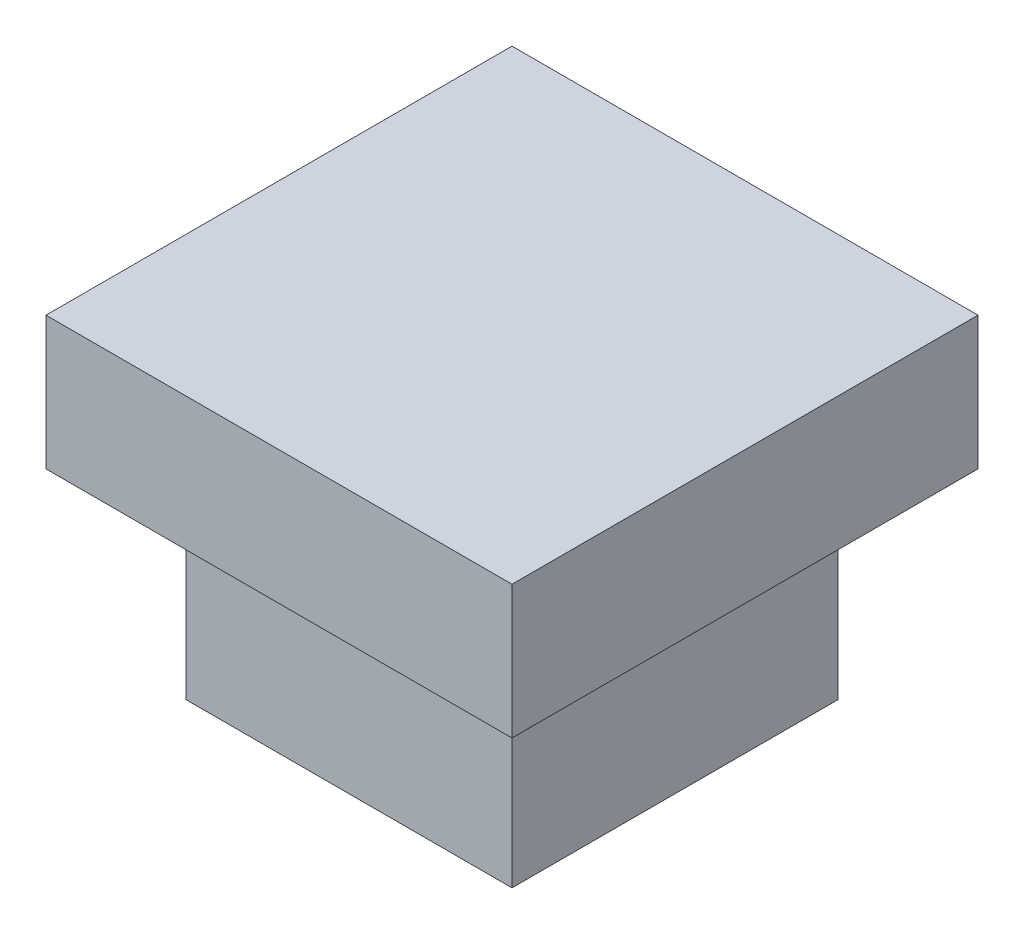
SolidWorks part; units mm, degrees
ref_plane "Alzado" through (0, 0, 0) normal (0, 0, 1) x (1, 0, 0)
ref_plane "Planta" through (0, 0, 0) normal (0, 1, 0) x (1, 0, 0)
ref_plane "Vista lateral" through (0, 0, 0) normal (1, 0, 0) x (0, 0, -1)
sketch "Croquis1" plane through (0, 0, 0) normal (0, 1, 0) x (1, 0, 0)
  line L1 (-2.45, -2.45) -> (2.45, -2.45)
  line L2 (-2.45, -2.45) -> (-2.45, 2.45)
  line L3 (-2.45, 2.45) -> (2.45, 2.45)
  line L4 (2.45, -2.45) -> (2.45, 2.45)
  line L5 (-2.45, -2.45) -> (2.45, 2.45) construction
  line L6 (-2.45, 2.45) -> (2.45, -2.45) construction
  point P0 (0, 0)
  dimension "D1" = 4.9
  dimension "D2" = 4.9
extrude "Saliente-Extruir1" add sketch "Croquis1" along normal blind 3
sketch "Croquis2" plane through (0, 3, 0) normal (0, 1, 0) x (1, 0, 0)
  line L1 (3.5, -3.5) -> (-3.5, -3.5)
  line L2 (3.5, -3.5) -> (3.5, 3.5)
  line L3 (3.5, 3.5) -> (-3.5, 3.5)
  line L4 (-3.5, -3.5) -> (-3.5, 3.5)
  line L5 (3.5, -3.5) -> (-3.5, 3.5) construction
  line L6 (3.5, 3.5) -> (-3.5, -3.5) construction
  point P0 (0, 0)
  dimension "D1" = 7
  dimension "D2" = 7
extrude "Saliente-Extruir2" add sketch "Croquis2" along normal blind 2
